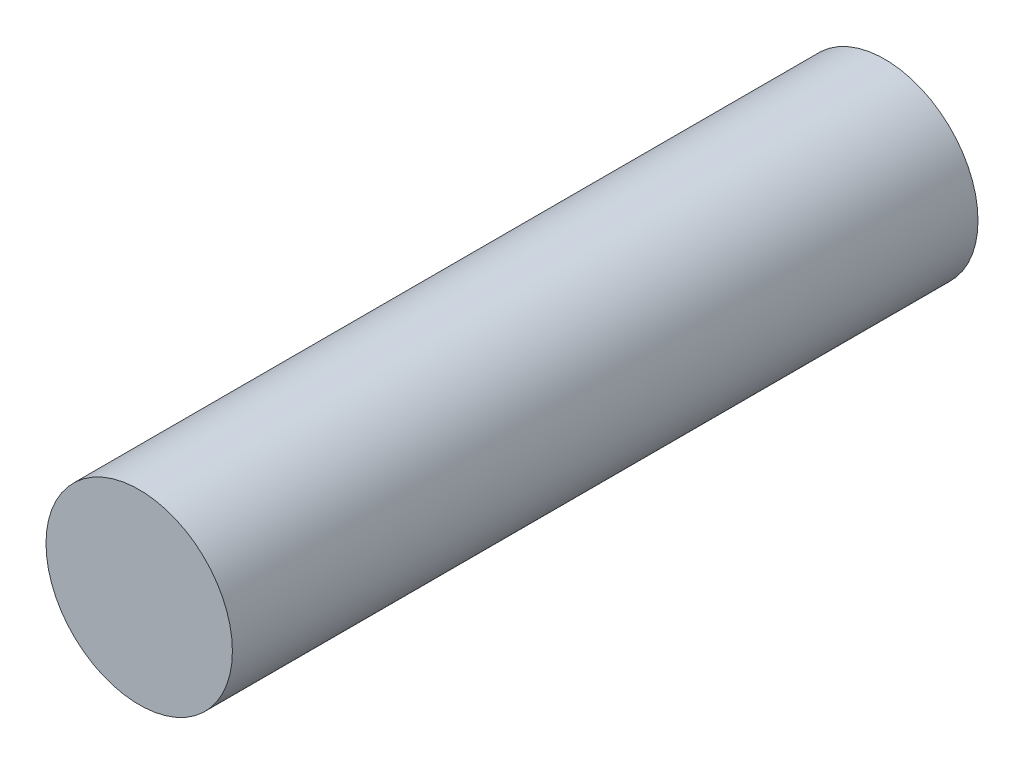
SolidWorks part; units mm, degrees
ref_plane "Front Plane" through (0, 0, 0) normal (0, 0, 1) x (1, 0, 0)
ref_plane "Top Plane" through (0, 0, 0) normal (0, 1, 0) x (1, 0, 0)
ref_plane "Right Plane" through (0, 0, 0) normal (1, 0, 0) x (0, 0, -1)
sketch "Sketch1" plane through (0, 0, 0) normal (0, 0, 1) x (1, 0, 0)
  circle A0 centre (0, 0) radius 5
  dimension "D1" = 10
extrude "Boss-Extrude1" add sketch "Sketch1" along normal blind 40
